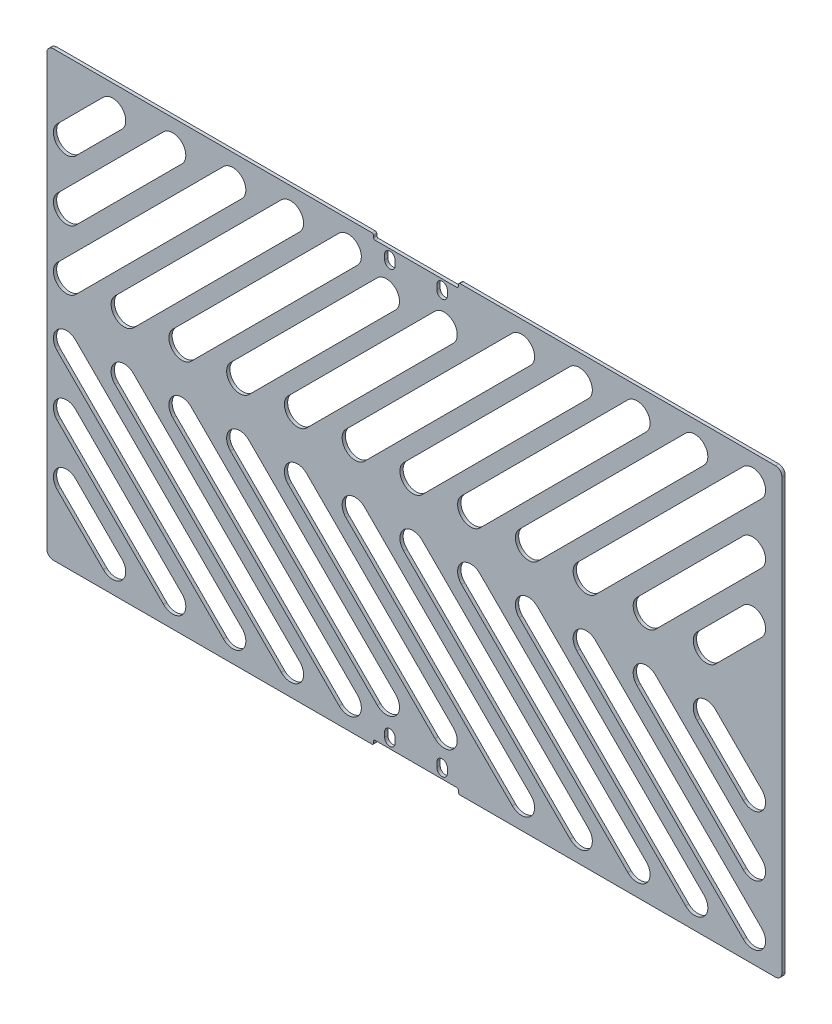
SolidWorks part; units mm, degrees
material "Thornel Mat VMA"
ref_plane "前视基准面" through (0, 0, 0) normal (0, 0, 1) x (1, 0, 0)
ref_plane "上视基准面" through (0, 0, 0) normal (0, 1, 0) x (1, 0, 0)
ref_plane "右视基准面" through (0, 0, 0) normal (1, 0, 0) x (0, 0, -1)
other "Configuration Table"
sketch "草图1" plane through (0, 0, 0) normal (0, 0, 1) x (1, 0, 0)
  line L1 (-112.5, 67.8) -> (112.5, 67.8)
  line L2 (-112.5, 67.8) -> (-112.5, -67.8)
  line L3 (-112.5, -67.8) -> (112.5, -67.8)
  line L4 (112.5, 67.8) -> (112.5, -67.8)
  line L5 (-112.5, 67.8) -> (112.5, -67.8) construction
  line L6 (-112.5, -67.8) -> (112.5, 67.8) construction
  point P0 (0, 0)
  dimension "D1" = 225
  dimension "D2" = 135.6
extrude "凸台-拉伸1" add sketch "草图1" along normal blind 1
sketch "草图2" plane through (0, 0, 1) normal (0, 0, 1) x (1, 0, 0)
  line L0 (-112.5, -67.8) -> (112.5, -67.8) construction
  line L1 (-7.5, -63.3) -> (8.5, -63.3) construction
  line L2 (-7.5, -63.3) -> (-7.5, -72.3) construction
  line L3 (-7.5, -72.3) -> (8.5, -72.3) construction
  line L4 (8.5, -63.3) -> (8.5, -72.3) construction
  line L5 (-7.5, -63.3) -> (8.5, -72.3) construction
  line L6 (-7.5, -72.3) -> (8.5, -63.3) construction
  line L7 (112.5, -67.8) -> (112.5, 67.8) construction
  line L8 (-12.5, -66.3) -> (13.5, -66.3)
  line L9 (-12.5, -66.3) -> (-12.5, -69.3)
  line L10 (-12.5, -69.3) -> (13.5, -69.3)
  line L11 (13.5, -66.3) -> (13.5, -69.3)
  line L12 (-12.5, -66.3) -> (13.5, -69.3) construction
  line L13 (-12.5, -69.3) -> (13.5, -66.3) construction
  line L14 (-7.5, -64.05) -> (-7.5, -62.55) construction
  line L15 (-9.1, -64.05) -> (-9.1, -62.55)
  line L16 (-5.9, -64.05) -> (-5.9, -62.55)
  line L17 (0.5, -77.0051) -> (0.5, -60.084) construction
  line L18 (8.5, -64.05) -> (8.5, -62.55) construction
  line L19 (10.1, -64.05) -> (10.1, -62.55)
  line L20 (6.9, -64.05) -> (6.9, -62.55)
  arc A0 (-9.1, -64.05) -> (-5.9, -64.05) centre (-7.5, -64.05) ccw
  arc A1 (-5.9, -62.55) -> (-9.1, -62.55) centre (-7.5, -62.55) ccw
  arc A2 (10.1, -64.05) -> (6.9, -64.05) centre (8.5, -64.05) cw
  arc A3 (6.9, -62.55) -> (10.1, -62.55) centre (8.5, -62.55) cw
  point P0 (0.5, -67.8)
  point P7 (0.5, -67.8)
  point P16 (-7.5, -63.3)
  point P25 (8.5, -63.3)
  dimension "D7" = 1.6
  dimension "D1" = 99
  dimension "D2" = 26
  dimension "D3" = 3
  dimension "D4" = 16
  dimension "D5" = 9
  dimension "D6" = 1.5
extrude "切除-拉伸1" cut sketch "草图2" against normal blind 1
mirror "镜向1" about plane through (0, 0, 0) normal (0, 1, 0) of "切除-拉伸1"
fillet "圆角1" radius 0.5 8 edges at (-12.5, -66.3, 0.5) (-12.5, -67.8, 0.5) (13.5, -67.8, 0.5) (13.5, -66.3, 0.5) (13.5, 67.8, 0.5) (13.5, 66.3, 0.5) (-12.5, 67.8, 0.5) (-12.5, 66.3, 0.5)
sketch "草图3" plane through (0, 0, 1) normal (0, 0, 1) x (1, 0, 0)
  line L0 (-17, 14.7394) -> (-17, -14.7394)
  line L1 (-10, -20.1556) -> (-10, -11)
  line L2 (-10, -11) -> (6.0297, -11)
  line L3 (22.1416, -4) -> (-10, -4)
  line L4 (-10, -4) -> (-10, 4)
  line L5 (-10, 4) -> (22.1416, 4)
  line L6 (6.0297, 11) -> (3.5, 11)
  line L7 (3.5, 11) -> (3.5, 22.2261)
  line L8 (-3.5, 22.2261) -> (-3.5, 11)
  line L9 (-3.5, 11) -> (-10, 11)
  line L10 (-10, 11) -> (-10, 20.1556)
  line L11 (-64.907, 0) -> (76.0769, 0) construction
  line L12 (21.0297, 8) -> (6.0297, 11)
  line L13 (21.0297, -8) -> (6.0297, -11)
  line L14 (3.5, 11) -> (-3.5, 11) construction
  line L15 (-10, 11) -> (-17, 11) construction
  line L16 (-10, -11) -> (-10, -4) construction
  line L17 (-10, 4) -> (-10, 11) construction
  circle A0 centre (0, 0) radius 22.5
  point P8 (17.6269, -15.2582)
  point P25 (0, 0)
  point P26 (11.165, -13.3864)
  point P27 (0, 11)
  point P28 (-12.9461, 5.4347)
  point P29 (-13.7798, -13)
  point P30 (0, 0)
  dimension "D1" = 45
  dimension "D2" = 7
  dimension "D3" = 8
  dimension "D4" = 10
  dimension "D5" = 4
  dimension "D6" = 15
extrude "切除-拉伸2" [suppressed] cut sketch "草图3" against normal blind 10 contours L5 A0 L12 L6 L7 L8 L9 L10 L0 L1 L2 L13 L3 L4
sketch "草图4" plane through (0, 0, 1) normal (0, 0, 1) x (1, 0, 0)
  line L0 (-112.5, -67.8) -> (-13, -67.8) construction
  line L1 (-100.25, -61.8) -> (-94, -58.1916)
  line L2 (-94, -58.1916) -> (-94, -50.9747)
  line L3 (-94, -50.9747) -> (-100.25, -47.3662)
  line L4 (-100.25, -47.3662) -> (-106.5, -50.9747)
  line L5 (-106.5, -50.9747) -> (-106.5, -58.1916)
  line L6 (-106.5, -58.1916) -> (-100.25, -61.8)
  line L7 (-106.5, -61.8) -> (106.5, -61.8)
  line L8 (-106.5, -61.8) -> (-106.5, 61.8)
  line L9 (-106.5, 61.8) -> (106.5, 61.8)
  line L10 (106.5, -61.8) -> (106.5, 61.8)
  line L11 (-112.5, 67.8) -> (-112.5, -67.8) construction
  line L12 (112.5, -67.8) -> (112.5, 67.8) construction
  line L14 (-12.5, -67.3) -> (13.5, -67.3)
  line L15 (-12.5, -67.3) -> (-12.5, -56.8)
  line L16 (-12.5, -56.8) -> (13.5, -56.8)
  line L17 (13.5, -67.3) -> (13.5, -56.8)
  line L18 (-12.5, 66.8) -> (13.5, 66.8)
  line L19 (-12.5, 66.8) -> (-12.5, 56.8)
  line L20 (-12.5, 56.8) -> (13.5, 56.8)
  line L21 (13.5, 66.8) -> (13.5, 56.8)
  line L25 (112.5, 67.8) -> (14, 67.8)
  line L26 (13.5, 67.3) -> (13.5, 66.8)
  line L27 (13, 66.3) -> (-12, 66.3)
  line L28 (-12.5, 66.8) -> (-12.5, 67.3)
  line L29 (-13, 67.8) -> (-112.5, 67.8)
  line L30 (-112.5, 67.8) -> (-112.5, -67.8)
  line L31 (-112.5, -67.8) -> (-13, -67.8)
  line L32 (-12.5, -67.3) -> (-12.5, -66.8)
  line L33 (-12, -66.3) -> (13, -66.3)
  line L34 (13.5, -66.8) -> (13.5, -67.3)
  line L35 (14, -67.8) -> (112.5, -67.8)
  line L36 (112.5, -67.8) -> (112.5, 67.8)
  line L37 (112.5, 67.8) -> (14, 67.8)
  line L38 (13.5, 67.3) -> (13.5, 66.8)
  line L39 (13, 66.3) -> (-12, 66.3)
  line L40 (-12.5, 66.8) -> (-12.5, 67.3)
  line L41 (-13, 67.8) -> (-112.5, 67.8)
  line L42 (-112.5, 67.8) -> (-112.5, -67.8)
  line L43 (-112.5, -67.8) -> (-13, -67.8)
  line L44 (-12.5, -67.3) -> (-12.5, -66.8)
  line L45 (-12, -66.3) -> (13, -66.3)
  line L46 (13.5, -66.8) -> (13.5, -67.3)
  line L47 (14, -67.8) -> (112.5, -67.8)
  line L48 (112.5, -67.8) -> (112.5, 67.8)
  circle A0 centre (-100.25, -54.5831) radius 6.25 construction
  arc A9 (14, 67.8) -> (13.5, 67.3) centre (14, 67.3) ccw
  arc A10 (13, 66.3) -> (13.5, 66.8) centre (13, 66.8) ccw
  arc A11 (-12.5, 66.8) -> (-12, 66.3) centre (-12, 66.8) ccw
  arc A12 (-12.5, 67.3) -> (-13, 67.8) centre (-13, 67.3) ccw
  arc A13 (-13, -67.8) -> (-12.5, -67.3) centre (-13, -67.3) ccw
  arc A14 (-12, -66.3) -> (-12.5, -66.8) centre (-12, -66.8) ccw
  arc A15 (13.5, -66.8) -> (13, -66.3) centre (13, -66.8) ccw
  arc A16 (13.5, -67.3) -> (14, -67.8) centre (14, -67.3) ccw
  arc A17 (14, 67.8) -> (13.5, 67.3) centre (14, 67.3) ccw
  arc A18 (13, 66.3) -> (13.5, 66.8) centre (13, 66.8) ccw
  arc A19 (-12.5, 66.8) -> (-12, 66.3) centre (-12, 66.8) ccw
  arc A20 (-12.5, 67.3) -> (-13, 67.8) centre (-13, 67.3) ccw
  arc A21 (-13, -67.8) -> (-12.5, -67.3) centre (-13, -67.3) ccw
  arc A22 (-12, -66.3) -> (-12.5, -66.8) centre (-12, -66.8) ccw
  arc A23 (13.5, -66.8) -> (13, -66.3) centre (13, -66.8) ccw
  arc A24 (13.5, -67.3) -> (14, -67.8) centre (14, -67.3) ccw
  dimension "D1" = 12.5
  dimension "D2" = 6
  dimension "D3" = 6
  dimension "D4" = 6
  dimension "D6" = 6
  dimension "D7" = 5
  dimension "D8" = 5
  dimension "D5" = 0
extrude "切除-拉伸3" [suppressed] cut sketch "草图4" against normal blind 10 contours L5 L6 L1 L2 L3 L4
other "填充阵列1" [suppressed] parameters "D5"=0, "D6"=0, "D1"=16, "D2"=60, "D3"=0, "D9"=115, "D7"=19, "D8"=10
sketch "草图5" plane through (0, 0, 1) normal (0, 0, 1) x (1, 0, 0)
  line L0 (-123.8684, 0) -> (145.9993, 0) construction
  line L1 (-106.5, -45.6579) -> (-92.3579, -59.8) construction
  line L2 (-103.6716, -42.8294) -> (-89.5294, -56.9716)
  line L3 (-109.3284, -48.4863) -> (-95.1863, -62.6284)
  line L4 (-106.5, -27.2731) -> (-73.9731, -59.8) construction
  line L5 (-103.6716, -24.4447) -> (-71.1447, -56.9716)
  line L6 (-109.3284, -30.1015) -> (-76.8015, -62.6284)
  line L7 (-106.5, -8.8883) -> (-55.5883, -59.8) construction
  line L8 (-103.6716, -6.0599) -> (-52.7599, -56.9716)
  line L9 (-109.3284, -11.7167) -> (-58.4167, -62.6284)
  line L10 (-112.5, -67.8) -> (-13, -67.8) construction
  line L11 (-112.5, 67.8) -> (-112.5, -67.8) construction
  line L12 (-88.8223, -8.8883) -> (-37.9106, -59.8) construction
  line L13 (-85.9939, -6.0599) -> (-35.0822, -56.9716)
  line L14 (-91.6508, -11.7167) -> (-40.7391, -62.6284)
  line L15 (-71.1447, -8.8883) -> (-20.233, -59.8) construction
  line L16 (-68.3162, -6.0599) -> (-17.4045, -56.9716)
  line L17 (-73.9731, -11.7167) -> (-23.0614, -62.6284)
  line L18 (-53.467, -8.8883) -> (-2.5553, -59.8) construction
  line L19 (-50.6386, -6.0599) -> (0.2731, -56.9716)
  line L20 (-56.2954, -11.7167) -> (-5.3837, -62.6284)
  line L21 (-35.7893, -8.8883) -> (15.1224, -59.8) construction
  line L22 (-32.9609, -6.0599) -> (17.9508, -56.9716)
  line L23 (-38.6177, -11.7167) -> (12.2939, -62.6284)
  line L24 (-18.1117, -8.8883) -> (32.8, -59.8) construction
  line L25 (-15.2832, -6.0599) -> (35.6285, -56.9716)
  line L26 (-20.9401, -11.7167) -> (29.9716, -62.6284)
  line L27 (-0.434, -8.8883) -> (50.4777, -59.8) construction
  line L28 (2.3944, -6.0599) -> (53.3061, -56.9716)
  line L29 (-3.2624, -11.7167) -> (47.6493, -62.6284)
  line L30 (17.2437, -8.8883) -> (68.1554, -59.8) construction
  line L31 (20.0721, -6.0599) -> (70.9838, -56.9716)
  line L32 (14.4153, -11.7167) -> (65.3269, -62.6284)
  line L33 (34.9214, -8.8883) -> (85.833, -59.8) construction
  line L34 (37.7498, -6.0599) -> (88.6615, -56.9716)
  line L35 (32.0929, -11.7167) -> (83.0046, -62.6284)
  line L36 (52.599, -8.8883) -> (103.5107, -59.8) construction
  line L37 (55.4275, -6.0599) -> (106.3391, -56.9716)
  line L38 (49.7706, -11.7167) -> (100.6823, -62.6284)
  line L40 (70.9838, -8.8883) -> (103.5107, -41.4152) construction
  line L41 (73.8122, -6.0599) -> (106.3391, -38.5868)
  line L42 (68.1554, -11.7167) -> (100.6823, -44.2437)
  line L43 (89.3686, -8.8883) -> (103.5107, -23.0304) construction
  line L44 (92.197, -6.0599) -> (106.3391, -20.202)
  line L45 (86.5402, -11.7167) -> (100.6823, -25.8589)
  arc A0 (-103.6716, -42.8294) -> (-109.3284, -48.4863) centre (-106.5, -45.6579) ccw
  arc A1 (-95.1863, -62.6284) -> (-89.5294, -56.9716) centre (-92.3579, -59.8) ccw
  arc A2 (-103.6716, -24.4447) -> (-109.3284, -30.1015) centre (-106.5, -27.2731) ccw
  arc A3 (-76.8015, -62.6284) -> (-71.1447, -56.9716) centre (-73.9731, -59.8) ccw
  arc A4 (-103.6716, -6.0599) -> (-109.3284, -11.7167) centre (-106.5, -8.8883) ccw
  arc A5 (-58.4167, -62.6284) -> (-52.7599, -56.9716) centre (-55.5883, -59.8) ccw
  arc A6 (-85.9939, -6.0599) -> (-91.6508, -11.7167) centre (-88.8223, -8.8883) ccw
  arc A7 (-40.7391, -62.6284) -> (-35.0822, -56.9716) centre (-37.9106, -59.8) ccw
  arc A8 (-68.3162, -6.0599) -> (-73.9731, -11.7167) centre (-71.1447, -8.8883) ccw
  arc A9 (-23.0614, -62.6284) -> (-17.4045, -56.9716) centre (-20.233, -59.8) ccw
  arc A10 (-50.6386, -6.0599) -> (-56.2954, -11.7167) centre (-53.467, -8.8883) ccw
  arc A11 (-5.3837, -62.6284) -> (0.2731, -56.9716) centre (-2.5553, -59.8) ccw
  arc A12 (-32.9609, -6.0599) -> (-38.6177, -11.7167) centre (-35.7893, -8.8883) ccw
  arc A13 (12.2939, -62.6284) -> (17.9508, -56.9716) centre (15.1224, -59.8) ccw
  arc A14 (-15.2832, -6.0599) -> (-20.9401, -11.7167) centre (-18.1117, -8.8883) ccw
  arc A15 (29.9716, -62.6284) -> (35.6285, -56.9716) centre (32.8, -59.8) ccw
  arc A16 (2.3944, -6.0599) -> (-3.2624, -11.7167) centre (-0.434, -8.8883) ccw
  arc A17 (47.6493, -62.6284) -> (53.3061, -56.9716) centre (50.4777, -59.8) ccw
  arc A18 (20.0721, -6.0599) -> (14.4153, -11.7167) centre (17.2437, -8.8883) ccw
  arc A19 (65.3269, -62.6284) -> (70.9838, -56.9716) centre (68.1554, -59.8) ccw
  arc A20 (37.7498, -6.0599) -> (32.0929, -11.7167) centre (34.9214, -8.8883) ccw
  arc A21 (83.0046, -62.6284) -> (88.6615, -56.9716) centre (85.833, -59.8) ccw
  arc A22 (55.4275, -6.0599) -> (49.7706, -11.7167) centre (52.599, -8.8883) ccw
  arc A23 (100.6823, -62.6284) -> (106.3391, -56.9716) centre (103.5107, -59.8) ccw
  arc A24 (73.8122, -6.0599) -> (68.1554, -11.7167) centre (70.9838, -8.8883) ccw
  arc A25 (100.6823, -44.2437) -> (106.3391, -38.5868) centre (103.5107, -41.4152) ccw
  arc A26 (92.197, -6.0599) -> (86.5402, -11.7167) centre (89.3686, -8.8883) ccw
  arc A27 (100.6823, -25.8589) -> (106.3391, -20.202) centre (103.5107, -23.0304) ccw
  circle A28 centre (-8.5553, -53.8) radius 4
  circle A29 centre (9.1224, -53.8) radius 4
  point P5 (-99.4289, -52.7289)
  point P12 (-90.2365, -43.5365)
  point P17 (-81.0442, -34.3442)
  point P24 (87.2473, -25.1518)
  point P25 (-63.3665, -34.3442)
  point P37 (-45.6888, -34.3442)
  point P44 (-28.0111, -34.3442)
  point P51 (-10.3335, -34.3442)
  point P58 (7.3442, -34.3442)
  point P65 (25.0219, -34.3442)
  point P72 (42.6995, -34.3442)
  point P79 (60.3772, -34.3442)
  point P86 (78.0549, -34.3442)
  point P98 (96.4396, -15.9594)
  point P107 (0, 0)
  dimension "D1" = 4
  dimension "D2" = 8
  dimension "D3" = 6
  dimension "D4" = 45
  dimension "D5" = 13
  dimension "D6" = 13
  dimension "D7" = 20
  dimension "D9" = 12.5
  dimension "D10" = 13
  dimension "D11" = 13
  dimension "D12" = 14
  dimension "D8" = 10
extrude "切除-拉伸4" cut sketch "草图5" against normal blind 10 contours L3 A1 L2 A0 | L6 A3 L5 A2 | L9 A5 L8 A4 | L14 A7 L13 A6 | L17 A9 L16 A8 | A28 L19 A10 L20 | A28 | A29 | A29 L22 A12 L23 | L26 A15 L25 A14 | L29 A17 L28 A16 | L32 A19 L31 A18 | L35 A21 L34 A20 | L38 A23 L37 A22 | L42 A25 L41 A24 | L45 A27 L44 A26
mirror "镜向2" about plane through (0, 0, 0) normal (0, 1, 0) of "切除-拉伸4"
fillet "圆角2" radius 2 4 edges at (112.5, 67.8, 0.5) (112.5, -67.8, 0.5) (-112.5, -67.8, 0.5) (-112.5, 67.8, 0.5)
